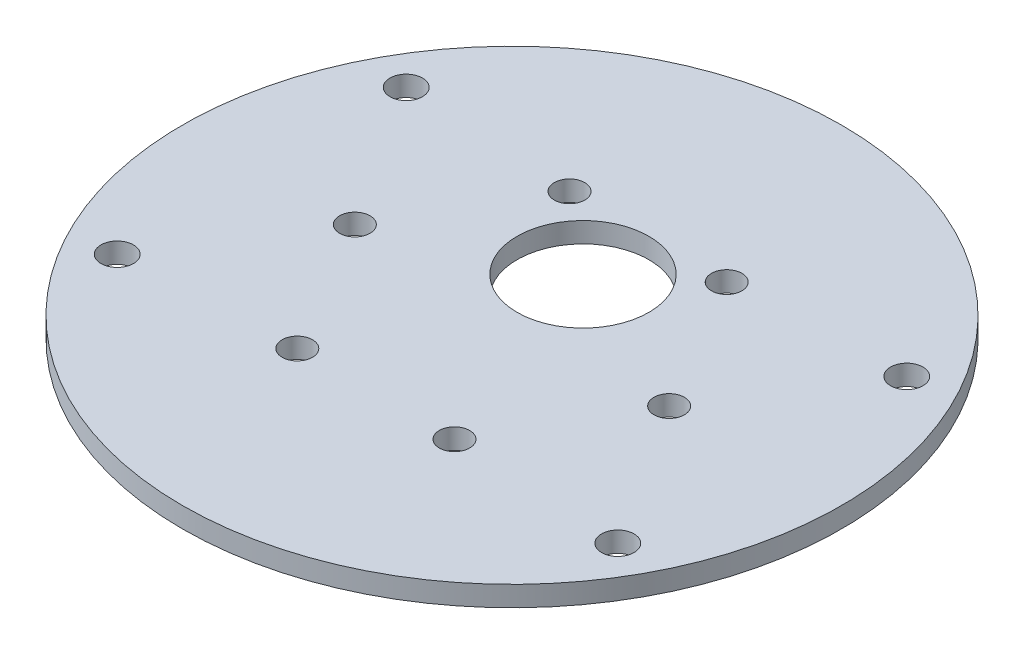
SolidWorks part; units mm, degrees
ref_plane "前视基准面" through (0, 0, 0) normal (0, 0, 1) x (1, 0, 0)
ref_plane "上视基准面" through (0, 0, 0) normal (0, 1, 0) x (1, 0, 0)
ref_plane "右视基准面" through (0, 0, 0) normal (1, 0, 0) x (0, 0, -1)
sketch "草图1" plane through (0, 0, 0) normal (0, 1, 0) x (1, 0, 0)
  line L0 (0, 0) -> (28.1458, -16.25) construction
  line L1 (0, 0) -> (32.5, 0) construction
  line L2 (0, 0) -> (0, -32.5) construction
  circle A0 centre (0, 0) radius 32.5
  circle A2 centre (-24.6817, -14.25) radius 1.6
  circle A3 centre (0, 7) radius 6.5
  circle A4 centre (24.6817, 14.25) radius 1.6
  circle A12 centre (24.6817, -14.25) radius 1.6
  circle A13 centre (-24.6817, 14.25) radius 1.6
  circle A16 centre (15.5, 0) radius 1.5 construction
  circle A17 centre (7.75, -13.4234) radius 1.5 construction
  circle A18 centre (-7.75, -13.4234) radius 1.5 construction
  circle A19 centre (-15.5, 0) radius 1.5 construction
  circle A20 centre (-7.75, 13.4234) radius 1.5 construction
  circle A21 centre (7.75, 13.4234) radius 1.5 construction
  circle A22 centre (15.5, 0) radius 1.5
  circle A23 centre (7.75, -13.4234) radius 1.5
  circle A24 centre (-7.75, -13.4234) radius 1.5
  circle A25 centre (-15.5, 0) radius 1.5
  circle A26 centre (-7.75, 13.4234) radius 1.5
  circle A27 centre (7.75, 13.4234) radius 1.5
  point P23 (-36.5619, -10.0911)
  point P35 (0, 0)
  dimension "D2" = 65
  dimension "D6" = 3.2
  dimension "D5" = 30
  dimension "D7" = 4
extrude "凸台-拉伸1" add sketch "草图1" along normal blind 2
